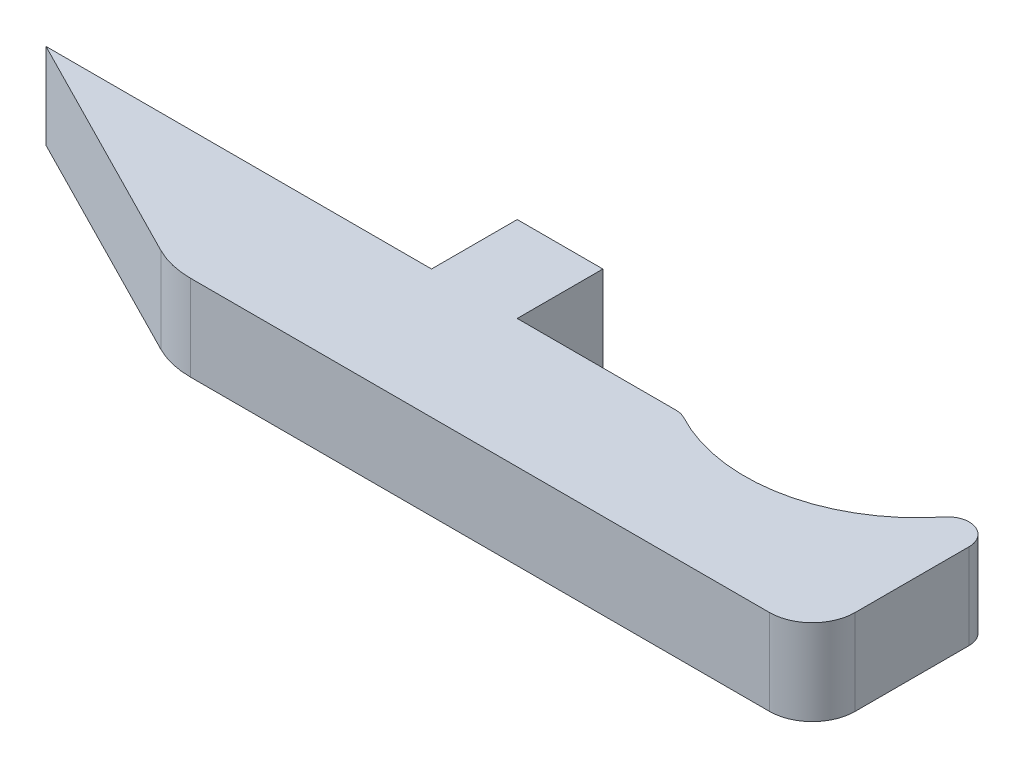
SolidWorks part; units mm, degrees
material "AISI 4130 Steel, annealed at 865C"
ref_plane "X-Y Datum" through (0, 0, 0) normal (0, 0, 1) x (1, 0, 0)
ref_plane "X-Z Datum" through (0, 0, 0) normal (0, 1, 0) x (1, 0, 0)
ref_plane "Y-Z Datum" through (0, 0, 0) normal (1, 0, 0) x (0, 0, -1)
sketch "Sketch1" plane through (0, 0, 0) normal (0, 1, 0) x (1, 0, 0)
  line L0 (59.0181, -15.392) -> (59.0181, 10.008) construction
  line L1 (59.0181, -13.8172) -> (3.2905, -13.8172)
  line L2 (59.0181, -13.8172) -> (59.0181, -2.692)
  line L3 (24.2201, -23.3422) -> (71.8451, -23.3422)
  line L4 (71.8451, -2.692) -> (71.8451, -23.3422)
  line L5 (5.5225, -13.8172) -> (24.2201, -23.3422)
  line L7 (34.0975, -13.8045) -> (2.3475, -13.8045) construction
  line L8 (34.0975, -13.8045) -> (2.3475, -13.8045)
  circle A0 centre (59.0181, -2.692) radius 12.827
  spline S0 degree 3 poles (59.0181, -15.392) (33.6181, -15.392) (33.6181, 10.008) (59.0181, 10.008) (84.4181, 10.008) (84.4181, -15.392) (59.0181, -15.392) (33.6181, -15.392) (33.6181, 10.008) knots -0.5 0 0 0 0.5 0.5 0.5 1 1 1 1.5 1.5 1.5 weights 1 0.333333 0.333333 1 0.333333 0.333333 1 0.333333 0.333333 only from (59.0181, -15.392) to (59.0181, -15.392)
  spline S1 degree 3 poles (59.0181, -15.392) (33.6181, -15.392) (33.6181, 10.008) (59.0181, 10.008) (84.4181, 10.008) (84.4181, -15.392) (59.0181, -15.392) (33.6181, -15.392) (33.6181, 10.008) knots -0.5 0 0 0 0.5 0.5 0.5 1 1 1 1.5 1.5 1.5 weights 1 0.333333 0.333333 1 0.333333 0.333333 1 0.333333 0.333333 only from (59.0181, -15.392) to (59.0181, -15.392) construction
  dimension "D3" = 25.654
  dimension "D5" = 9.525
  dimension "D1" = 55.7276
  dimension "D2" = 11.1252
  dimension "D4" = 3.175
  dimension "D6" = 47.625
extrude "Boss-Extrude1" add sketch "Sketch1" along normal blind 6.35
fillet "Fillet1" radius 1.5875 2 edges at (52.6336, 3.175, 13.8172) (71.8451, 3.175, 2.692)
fillet "Fillet2" radius 6.35 1 edges at (24.2201, 3.175, 23.3422)
fillet "Fillet3" radius 3.175 1 edges at (71.8451, 3.175, 23.3422)
sketch "Sketch6" plane through (0, 0, 13.8172) normal (0, 0, -1) x (-1, 0, 0)
  line L0 (-52.2236, 6.35) -> (-5.5225, 6.35) construction
  line L1 (-40.4475, 6.35) -> (-34.0975, 6.35)
  line L2 (-40.4475, 6.35) -> (-40.4475, 0)
  line L3 (-40.4475, 0) -> (-34.0975, 0)
  line L4 (-34.0975, 6.35) -> (-34.0975, 0)
  line L5 (-52.2236, 0) -> (-5.5225, 0) construction
  line L6 (-5.5225, 6.35) -> (-5.5225, 0) construction
  dimension "D1" = 6.35
  dimension "D2" = 28.575
extrude "Boss-Extrude2" add sketch "Sketch6" along normal blind 6.35
fillet "Fillet4" [suppressed] radius 0.7937
